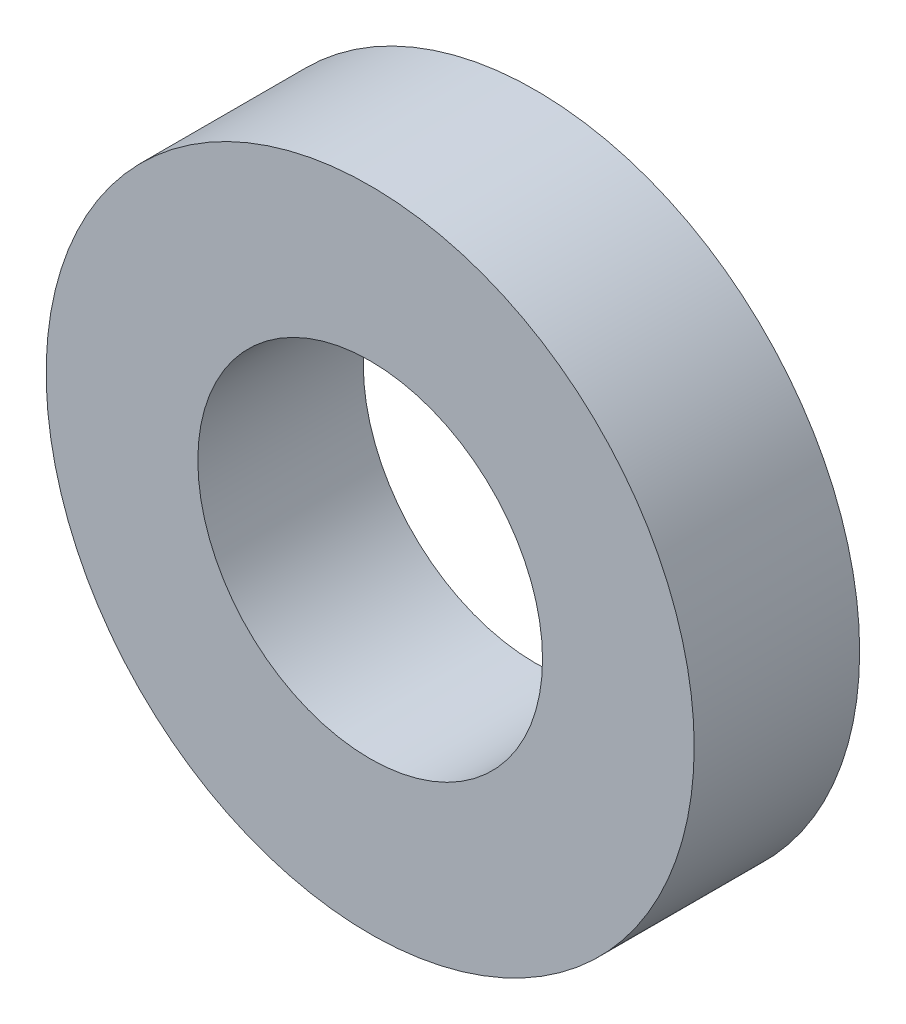
SolidWorks part; units mm, degrees
material "Polylactide (PLA)"
ref_plane "Front Plane" through (0, 0, 0) normal (0, 0, 1) x (1, 0, 0)
ref_plane "Top Plane" through (0, 0, 0) normal (0, 1, 0) x (1, 0, 0)
ref_plane "Right Plane" through (0, 0, 0) normal (1, 0, 0) x (0, 0, -1)
sketch "Sketch1" plane through (0, 0, 0) normal (0, 0, 1) x (1, 0, 0)
  circle A0 centre (0, 0) radius 12.5
  circle A1 centre (0, 0) radius 23.5
  dimension "D1" = 25
  dimension "D2" = 47
extrude "Boss-Extrude1" add sketch "Sketch1" along normal blind 12
